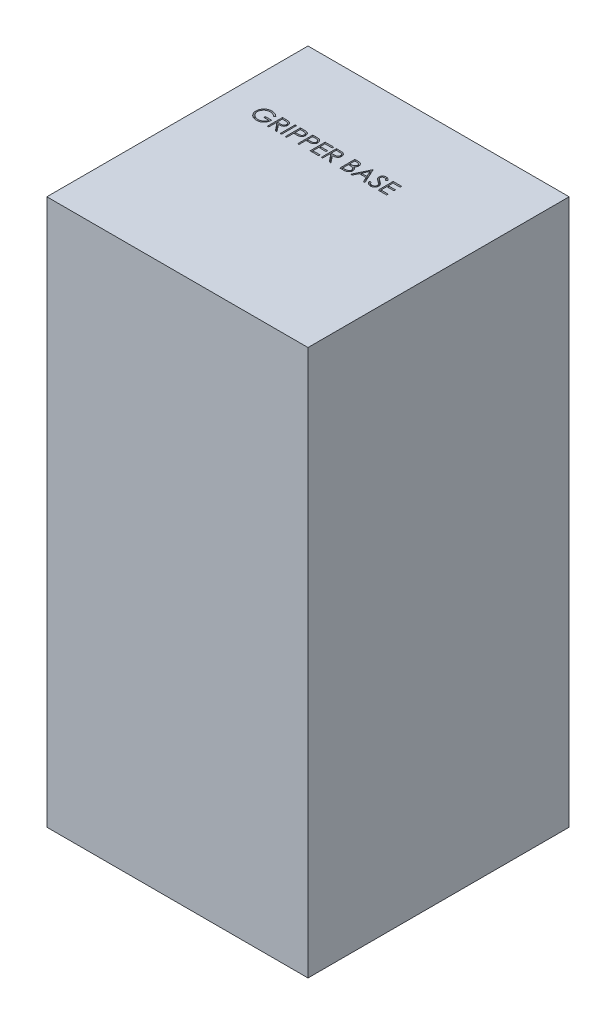
SolidWorks part; units mm, degrees
ref_plane "Front Plane" through (0, 0, 0) normal (0, 0, 1) x (1, 0, 0)
ref_plane "Top Plane" through (0, 0, 0) normal (0, 1, 0) x (1, 0, 0)
ref_plane "Right Plane" through (0, 0, 0) normal (1, 0, 0) x (0, 0, -1)
sketch "Sketch1" plane through (0, 0, 0) normal (0, 1, 0) x (1, 0, 0)
  line L1 (-27.5, -27.5) -> (27.5, -27.5)
  line L2 (-27.5, -27.5) -> (-27.5, 27.5)
  line L3 (-27.5, 27.5) -> (27.5, 27.5)
  line L4 (27.5, -27.5) -> (27.5, 27.5)
  line L5 (-27.5, -27.5) -> (27.5, 27.5) construction
  line L6 (-27.5, 27.5) -> (27.5, -27.5) construction
  point P0 (0, 0)
  dimension "D1" = 55
  dimension "D2" = 55
extrude "Boss-Extrude1" add sketch "Sketch1" along normal blind 115
sketch "Sketch2" plane through (0, 115, 0) normal (0, 1, 0) x (1, 0, 0)
  text T0 "GRIPPER BASE "
extrude "Cut-Extrude1" cut sketch "Sketch2" against normal blind 1
